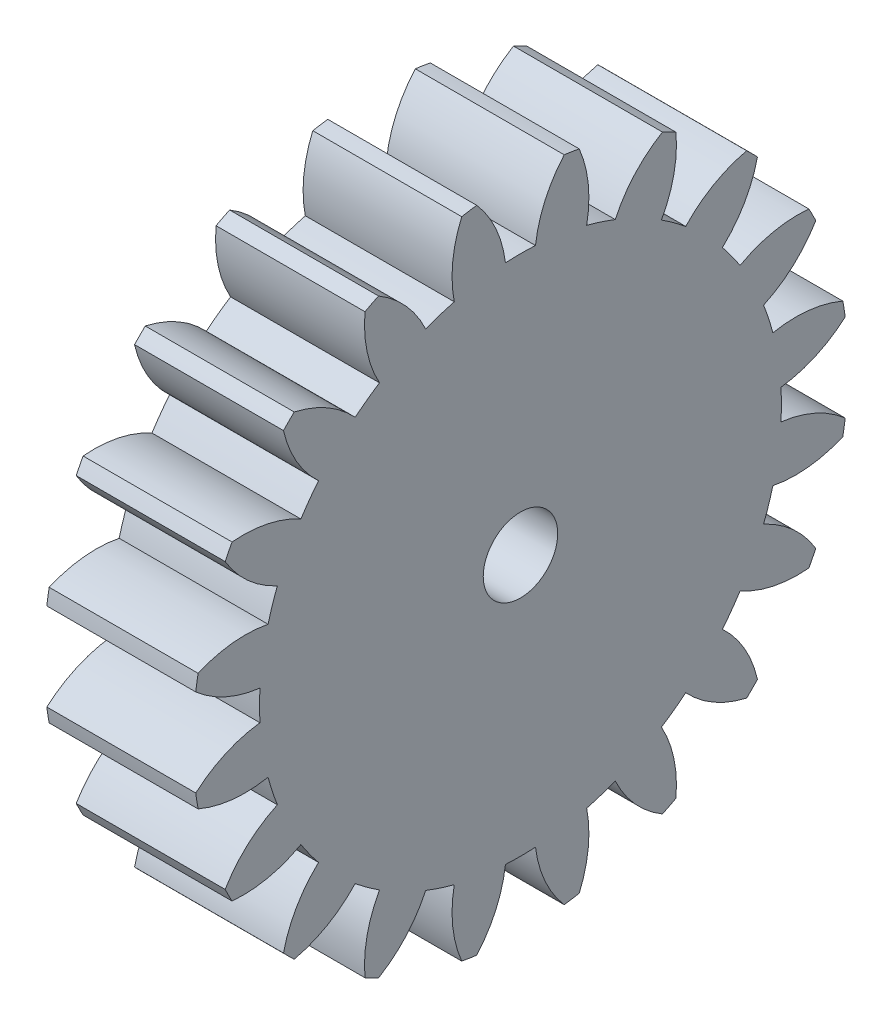
SolidWorks part; units mm, degrees
ref_plane "Plane1" through (0, 0, 0) normal (0, 0, 1) x (1, 0, 0)
ref_plane "Plane2" through (0, 0, 0) normal (0, 1, 0) x (1, 0, 0)
ref_plane "Plane3" through (0, 0, 0) normal (1, 0, 0) x (0, 0, -1)
sketch "HoldingSke" plane through (0, 0, 0) normal (0, 1, 0) x (1, 0, 0)
  line L0 (0, 0) -> (477.3639, -173.7462)
  line L1 (-15, 0) -> (100, 0) construction
  line L2 (0, 0) -> (-2.1039, 2.3779)
  line L3 (0, 0) -> (-11.863, 4.5341)
  line L4 (0, 0) -> (8.1152, 2.9537)
  line L5 (0, 0) -> (-47.5972, -17.7524)
  line L6 (0, 0) -> (-5.2639, -3.5516)
  line L7 (-2.1039, 2.3779) -> (8.8308, 51.9871)
  line L8 (-76.2, 54.61) -> (-72.771, 54.61)
  line L9 (-71.009, 38.7566) -> (-53.1078, 45.2721)
  line L10 (-76.2, 71.12) -> (104.1128, 71.12)
  line L11 (0, 0) -> (-6.35, 0)
  line L12 (-76.2, 101.6) -> (-76.1492, 101.6)
  line L13 (24.9733, 27.94) -> (52.9518, 28.4284)
  line L14 (24.9733, 27.94) -> (25.0241, 27.9398)
  line L15 (24.9733, 27.94) -> (100.4021, 29.52)
  circle A0 centre (0, 0) radius 1.5875
  circle A1 centre (0, 0) radius 11.1252
  circle A2 centre (0, 0) radius 38.1
  circle A3 centre (0, 0) radius 1.5875
  dimension "MHD" = 22.2504
  dimension "Hub_dia" = 76.2
  dimension "Bore" = 3.175
  dimension "MBD" = 3.175
  dimension "Num_teeth" = 20
  dimension "Pitch" = 508
  dimension "Overall_len" = 50.8
  dimension "Show_teeth" = 20
  dimension "Thickness" = 6.35
  dimension "OAL" = 50.8001
  dimension "T_dim" = 3.429
  dimension "Ap" = 20
  dimension "H" = 19.05
  dimension "Pitch_radius" = 180.3128
  dimension "Width" = 6.35
  dimension "Backlash" = 0.0508
  dimension "Addendum_fac" = 1
  dimension "Dedendum_fac" = 1.2
  dimension "Clearance_fac" = 0.2
  dimension "Dedendum_add" = 0.0508
sketch "BasProSke" plane through (0, 0, 0) normal (0, 1, 0) x (1, 0, 0)
  line L0 (-10, 0) -> (60, 0) construction
  line L1 (0, 0) -> (0, 13.97)
  line L2 (0, 0) -> (6.35, 0)
  line L3 (6.35, 0) -> (6.35, 13.97)
  line L4 (6.35, 13.97) -> (0, 13.97)
  dimension "Thickness" = 6.35
  dimension "Diameter" = 27.94
revolve "Base-Revolve" add sketch "BasProSke" angle 360 about L0
sketch "TooCutSke" plane through (0, 0, 0) normal (1, 0, 0) x (0, 0, -1)
  line L1 (0, 0) -> (0, 107) construction
  line L2 (0, 0) -> (-1.0853, 12.6535) construction
  line L3 (0, 0) -> (-3.9633, 25.0231) construction
  line L4 (-1.0853, 12.6535) -> (-1.9816, 12.5116) construction
  arc A0 (0.6405, 11.1067) -> (-0.6405, 11.1067) centre (0, 0) ccw
  arc A1 (1.8856, 13.8678) -> (-1.8856, 13.8678) centre (0, 0) ccw
  circle A2 centre (0, 0) radius 12.7 construction
  circle A3 centre (0, 0) radius 11.9341 construction
  arc A4 (-0.6405, 11.1067) -> (-1.8856, 13.8678) centre (-5.6834, 10.4939) ccw
  arc A5 (1.8856, 13.8678) -> (0.6405, 11.1067) centre (5.6834, 10.4939) ccw
  dimension "Root_dia" = 22.2504
  dimension "Overcut_dia" = 27.9908
  dimension "Pitch_dia" = 25.4
  dimension "Base_dia" = 23.8682
  dimension "Flank_rad" = 5.08
  dimension "Half_ang" = 9
  dimension "Half_CT" = 0.9075
extrude "ToothCut" cut sketch "TooCutSke" along normal through all
fillet "Breaks" [suppressed] radius 0.0254
fillet "RootFillets" [suppressed] radius 0.3048
pattern_circular "TeethCuts" count 20 every 18 about axis through (-10, 0, 0) along (1, 0, 0) of "ToothCut", "RootFillets", "Breaks"
sketch "HubNeaOneSke" plane through (0, 0, 0) normal (-1, 0, 0) x (0, 0, 1)
  circle A0 centre (0, 0) radius 11.1252
  dimension "Diameter" = 22.2504
extrude "HubNearOne" [suppressed] add sketch "HubNeaOneSke" along normal blind 44.4501
sketch "HubNeaBotSke" plane through (0, 0, 0) normal (-1, 0, 0) x (0, 0, 1)
  circle A0 centre (0, 0) radius 11.1252
  dimension "Diameter" = 22.2504
extrude "HubNearBoth" [suppressed] add sketch "HubNeaBotSke" along normal blind 22.225
ref_plane "FarPln" through (6.35, 0, 0) normal (1, 0, 0) x (0, 0, -1)
sketch "HubFarSke" plane through (6.35, 0, 0) normal (1, 0, 0) x (0, 0, -1)
  circle A0 centre (0, 0) radius 11.1252
  dimension "Diameter" = 22.2504
extrude "HubFar" [suppressed] add sketch "HubFarSke" along normal blind 22.225
sketch "BorSke" plane through (0, 0, 0) normal (1, 0, 0) x (0, 0, -1)
  circle A0 centre (0, 0) radius 1.5875
  dimension "Diameter" = 3.175
extrude "Bore" cut sketch "BorSke" along normal mid plane 101.6001
sketch "KeySke" plane through (0, 0, 0) normal (1, 0, 0) x (0, 0, -1)
  line L0 (-0.127, 0) -> (-0.127, 1.8415)
  line L1 (-0.127, 1.8415) -> (0.127, 1.8415)
  line L2 (0.127, 1.8415) -> (0.127, 0)
  line L3 (0, 0) -> (0, 34) construction
  line L4 (-0.127, 0) -> (0.127, 0)
  dimension "Offset" = 1.8415
  dimension "Width" = 0.254
extrude "Keyway" [suppressed] cut sketch "KeySke" along normal mid plane 101.6001
pattern_circular "Keyway2" [suppressed] count 2 every 90 about axis through (-10, 0, 0) along (1, 0, 0)
equation "' \"Pitch@HoldingSke\" = 4"
equation "' \"Num_teeth@HoldingSke\" = 12"
equation "' \"Ap@HoldingSke\" =  20"
equation "' \"Ap@HoldingSke\" = 20"
equation "' \"Width@HoldingSke\" = 0.5"
equation "' \"Hub_dia@HoldingSke\"= 1"
equation "' \"Hub_dia@HoldingSke\" = 1"
equation "' \"Overall_len@HoldingSke\" = 1.0"
equation "' \"Bore@HoldingSke\" = 0.75"
equation "' \"T_dim@HoldingSke\" = 0.85"
equation "' \"Width@KeySke\" = 0.25"
equation "' \"Show_teeth@HoldingSke\" = 13"
equation "' \"Backlash@HoldingSke\" = 0.009"
equation "' \"Addendum_fac@HoldingSke\" = 1.0"
equation "' \"Dedendum_fac@HoldingSke\" = 1.25"
equation "' \"Dedendum_add@HoldingSke\" = 0.00005"
equation "' \"Clearance_fac@HoldingSke\" = 0.25"
equation "' \"Pitch@HoldingSke\" = 0.5"
equation "' \"Num_teeth@HoldingSke\" = 23"
equation "' \"Show_teeth@HoldingSke\" = 23"
equation "' \"Backlash@HoldingSke\" = 0.0375"
equation "\"Overcut_dia@TooCutSke\" = (\"Num_teeth@HoldingSke\" + 2 * \"Addendum_fac@HoldingSke\") / \"Pitch@HoldingSke\" + 0.002"
equation "\"Pitch_dia@TooCutSke\" = \"Num_teeth@HoldingSke\" / \"Pitch@HoldingSke\""
equation "\"Base_dia@TooCutSke\" = \"Num_teeth@HoldingSke\" / \"Pitch@HoldingSke\" * cos((\"Ap@HoldingSke\"  * 3.14159265 / 180))"
equation "\"Root_dia@TooCutSke\" = (\"Num_teeth@HoldingSke\" + 2) / \"Pitch@HoldingSke\" - 2 * (\"Addendum_fac@HoldingSke\" + \"Dedendum_fac@HoldingSke\") / \"Pitch@HoldingSke\" - \"Dedendum_add@HoldingSke\" * 2"
equation "\"Half_ang@TooCutSke\" = 180 / \"Num_teeth@HoldingSke\""
equation "\"Half_CT@TooCutSke\" = \"Num_teeth@HoldingSke\" / \"Pitch@HoldingSke\" * sin((3.14159265 / 2 / \"Num_teeth@HoldingSke\")) / 2 - 7 * \"Backlash@HoldingSke\" / 4"
equation "\"Flank_rad@TooCutSke\" = \"Num_teeth@HoldingSke\" / \"Pitch@HoldingSke\" / 5"
equation "\"Radius@RootFillets\" = \"Clearance_fac@HoldingSke\" / \"Pitch@HoldingSke\" + \"Dedendum_add@HoldingSke\""
equation "\"Break_rad@Breaks\" = 0.02 / \"Pitch@HoldingSke\""
equation "\"Thickness@HoldingSke\" = \"Width@HoldingSke\""
equation "\"OAL@HoldingSke\" = \"Thickness@HoldingSke\""
equation "\"MHD@HoldingSke\" = (\"Num_teeth@HoldingSke\" + 2) / \"Pitch@HoldingSke\" - 2 * (\"Addendum_fac@HoldingSke\" + \"Dedendum_fac@HoldingSke\")  / \"Pitch@HoldingSke\" - \"Dedendum_add@HoldingSke\" * 2"
equation "\"MBD@HoldingSke\" = (\"Num_teeth@HoldingSke\" + 2) / \"Pitch@HoldingSke\" - 2 * (\"Addendum_fac@HoldingSke\" + \"Dedendum_fac@HoldingSke\")  / \"Pitch@HoldingSke\" - \"Dedendum_add@HoldingSke\" * 2 - 0.002"
equation "\"MHD@HoldingSke\" = ((sgn( \"MHD@HoldingSke\" - \"Hub_dia@HoldingSke\" )-1)*( \"MHD@HoldingSke\" - \"Hub_dia@HoldingSke\" ))/-2+ \"Hub_dia@HoldingSke\""
equation "\"MBD@HoldingSke\" = ((sgn( \"MBD@HoldingSke\" - \"Bore@HoldingSke\" )-1)*( \"MBD@HoldingSke\" - \"Bore@HoldingSke\" ))/-2+ \"Bore@HoldingSke\""
equation "\"OAL@HoldingSke\" = ((sgn( \"OAL@HoldingSke\" - \"Overall_len@HoldingSke\" )+1)*( \"OAL@HoldingSke\" - \"Overall_len@HoldingSke\" ))/2 + \"Overall_len@HoldingSke\" + 0.000002"
equation "\"Num_teeth@TeethCuts\" = int( \"Show_teeth@HoldingSke\" ) + 1"
equation "\"Num_teeth@TeethCuts\" = ((sgn( \"Num_teeth@TeethCuts\" - \"Num_teeth@HoldingSke\" )-1)*( \"Num_teeth@TeethCuts\" - \"Num_teeth@HoldingSke\" ))/-2+ \"Num_teeth@HoldingSke\""
equation "\"Num_teeth@TeethCuts\" = ((sgn( \"Num_teeth@TeethCuts\" - 2.0)+1)*( \"Num_teeth@TeethCuts\" - 2.0))/2 +2.0"
equation "\"Angle@TeethCuts\" = 360.0 / \"Num_teeth@HoldingSke\""
equation "\"Diameter@BasProSke\" = (\"Num_teeth@HoldingSke\" + 2 * \"Addendum_fac@HoldingSke\") / \"Pitch@HoldingSke\""
equation "\"Thickness@BasProSke\"  = \"Thickness@HoldingSke\""
equation "' \"Fillet_rad@BasProSke\" =  \"Thickness@HoldingSke\" * 0.05"
equation "' \"Fillet_rad@BasProSke\" = \"Thickness@HoldingSke\" * 0.05"
equation "\"MHD@HoldingSke\" = ((sgn( \"MHD@HoldingSke\" - \"Root_dia@TooCutSke\" )-1)*( \"MHD@HoldingSke\" - \"Root_dia@TooCutSke\" ))/-2+ \"Root_dia@TooCutSke\""
equation "\"Diameter@HubNeaOneSke\" = \"MHD@HoldingSke\""
equation "\"Length@HubNearOne\" = \"OAL@HoldingSke\" - \"Thickness@BasProSke\""
equation "\"Diameter@HubNeaBotSke\" = \"MHD@HoldingSke\""
equation "\"Length@HubNearBoth\" = ( \"OAL@HoldingSke\" - \"Thickness@BasProSke\" ) / 2.0"
equation "\"Thickness@FarPln\" = \"Thickness@BasProSke\""
equation "\"Diameter@HubFarSke\" = \"MHD@HoldingSke\""
equation "\"Length@HubFar\" = ( \"OAL@HoldingSke\" - \"Thickness@BasProSke\" ) / 2.0"
equation "\"Diameter@BorSke\" = \"MBD@HoldingSke\""
equation "\"D1@Bore\" = \"OAL@HoldingSke\" * 2.0"
equation "\"D1@Keyway\" = \"OAL@HoldingSke\" * 2.0"
equation "\"Offset@KeySke\" = \"T_dim@HoldingSke\" - \"MBD@HoldingSke\" / 2.0"
